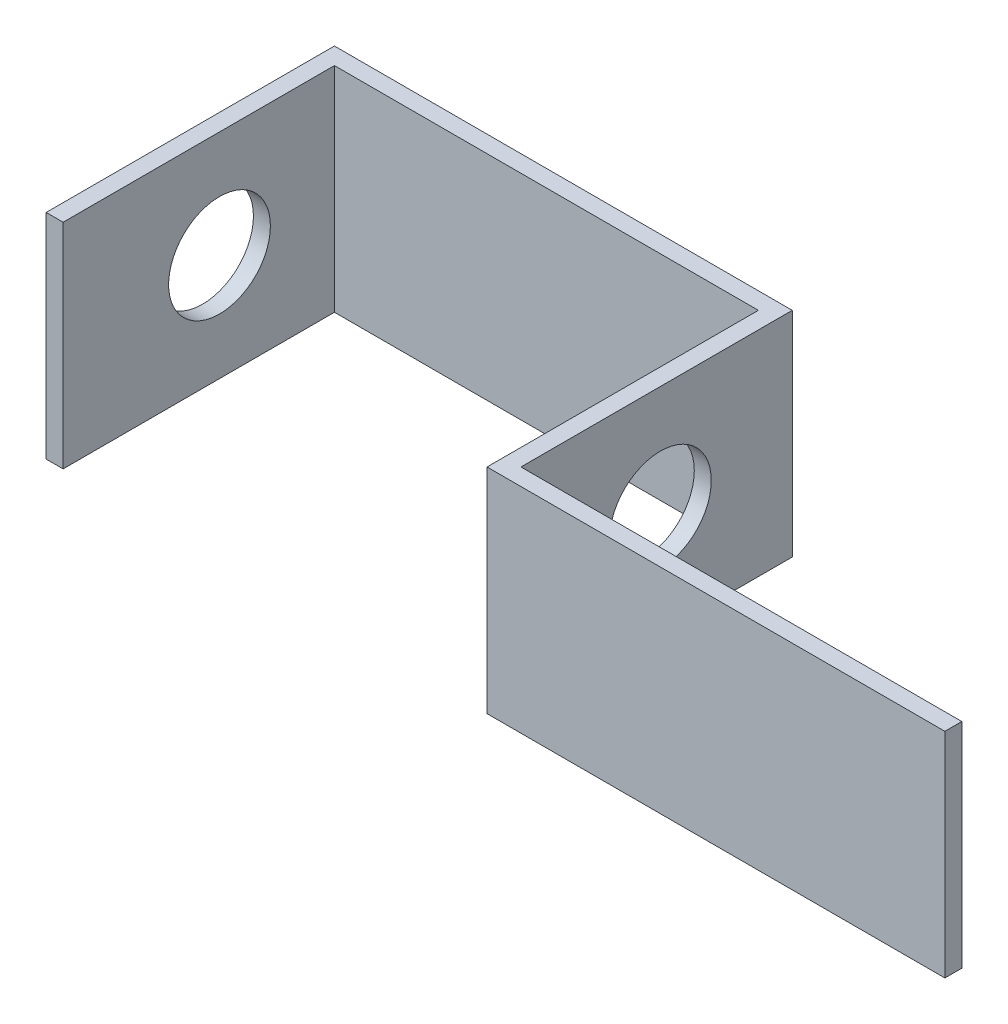
SolidWorks part; units mm, degrees
ref_plane "Front Plane" through (0, 0, 0) normal (0, 0, 1) x (1, 0, 0)
ref_plane "Top Plane" through (0, 0, 0) normal (0, 1, 0) x (1, 0, 0)
ref_plane "Right Plane" through (0, 0, 0) normal (1, 0, 0) x (0, 0, -1)
sketch "Sketch1" plane through (0, 0, 0) normal (0, 1, 0) x (1, 0, 0)
  line L0 (-79.375, 23.7753) -> (-85.725, 23.7753) construction
  line L2 (85.725, 0) -> (85.725, 101.6)
  line L3 (85.725, 101.6) -> (-85.725, 101.6)
  line L4 (-85.725, -6.35) -> (-85.725, 101.6)
  line L5 (75.2085, -89.136) -> (-85.725, 101.6) construction
  line L6 (85.725, 101.6) -> (-75.2085, -89.136) construction
  line L11 (75.2085, -89.136) -> (-75.2085, -89.136) construction
  line L13 (79.375, 95.25) -> (-79.375, 95.25)
  line L14 (79.375, 95.25) -> (79.375, -6.35)
  line L16 (-79.375, 95.25) -> (-79.375, -6.35)
  line L17 (69.6951, 95.25) -> (69.6951, 101.6) construction
  line L18 (79.375, 35.2348) -> (85.725, 35.2348) construction
  line L21 (110.0881, -6.35) -> (250.825, -6.35)
  line L22 (250.825, -6.35) -> (250.825, 0)
  line L23 (250.825, 0) -> (85.725, 0)
  line L24 (110.0881, -6.35) -> (79.375, -6.35)
  line L25 (-79.375, -6.35) -> (-85.725, -6.35)
  point P0 (0, 0)
  point P6 (165.1, -79.375)
  point P7 (0, 0)
  dimension "D1" = 171.45
  dimension "D2" = 6.35
  dimension "D3" = 101.6
  dimension "D4" = 171.45
extrude "Boss-Extrude1" add sketch "Sketch1" along normal blind 80.01
sketch "Sketch2" plane through (85.725, 0, 0) normal (1, 0, 0) x (0, 0, -1)
  circle A0 centre (52.2149, 40.005) radius 19.05
  dimension "D1" = 38.1
extrude "Cut-Extrude1" cut sketch "Sketch2" against normal blind 175.768
